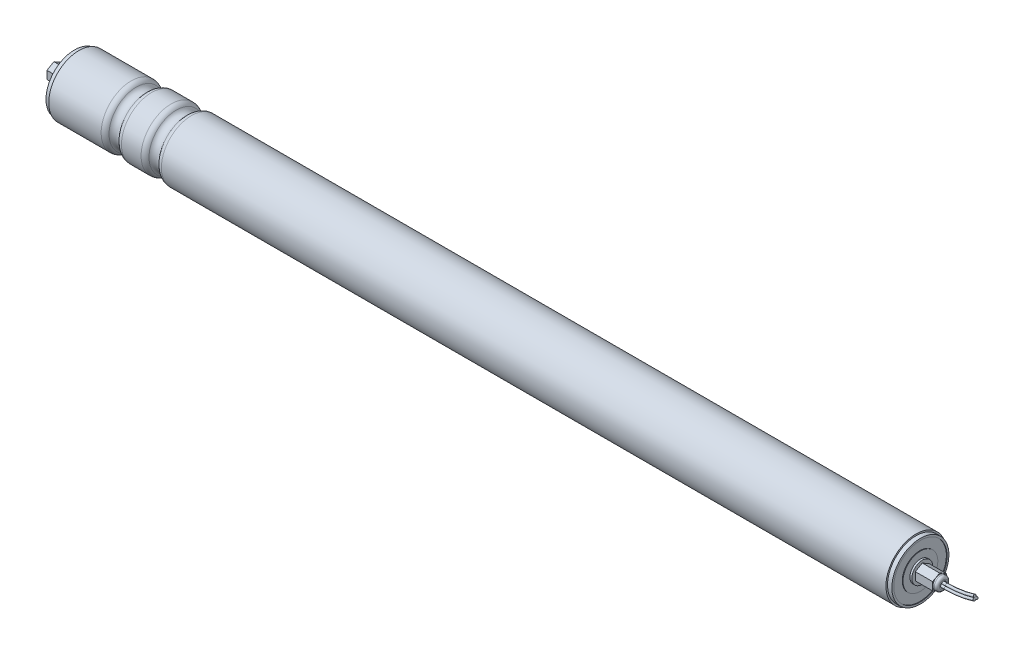
SolidWorks part; units mm, degrees
ref_plane "Front Plane" through (0, 0, 0) normal (0, 0, 1) x (1, 0, 0)
ref_plane "Top Plane" through (0, 0, 0) normal (0, 1, 0) x (1, 0, 0)
ref_plane "Right Plane" through (0, 0, 0) normal (1, 0, 0) x (0, 0, -1)
sketch "Sketch1" plane through (0, 0, 0) normal (0, 0, 1) x (1, 0, 0)
  line L0 (-340.407, 0) -> (340.407, 0) construction
  line L1 (-340.407, 0) -> (-355.393, 0) construction
  line L2 (340.407, 0) -> (357.425, 0) construction
  line L3 (-342.9, 0) -> (-340.407, 0) construction
  line L4 (340.407, 0) -> (342.9, 0) construction
  point P2 (-342.9, 0)
  point P6 (342.9, 0)
  point P7 (-335.407, 0)
  point P8 (335.407, 0)
  dimension "D1" = 17.018
  dimension "D2" = 14.986
  dimension "D3" = 5
  dimension "D4" = 5
  dimension "BF" = 685.8
  dimension "D5" = 670.814
sketch "Sketch2" plane through (0, 0, 0) normal (0, 0, 1) x (1, 0, 0)
  line L0 (-340.407, 0) -> (-340.407, 8.382)
  line L1 (-340.407, 8.382) -> (-338.883, 8.382)
  line L2 (-338.883, 8.382) -> (-338.883, 13.97)
  line L3 (-338.883, 13.97) -> (-338.375, 13.97)
  line L4 (-338.375, 13.97) -> (-338.375, 21.336)
  line L5 (-338.375, 21.336) -> (-338.883, 21.336)
  line L6 (-338.883, 21.336) -> (-338.883, 22.86)
  line L7 (-338.883, 22.86) -> (-335.407, 22.86)
  line L8 (-335.407, 22.86) -> (-335.407, 0)
  line L9 (-340.407, 0) -> (340.407, 0) construction
  line L10 (-335.407, 0) -> (-340.407, 0)
  line L11 (-340.407, 0) -> (-355.393, 0) construction
  line L12 (0, 0) -> (0, 29.0055) construction
  line L13 (335.407, 0) -> (340.407, 0)
  line L14 (335.407, 22.86) -> (335.407, 0)
  line L15 (338.883, 22.86) -> (335.407, 22.86)
  line L16 (338.883, 21.336) -> (338.883, 22.86)
  line L17 (338.375, 21.336) -> (338.883, 21.336)
  line L18 (338.375, 13.97) -> (338.375, 21.336)
  line L19 (338.883, 13.97) -> (338.375, 13.97)
  line L20 (338.883, 8.382) -> (338.883, 13.97)
  line L21 (340.407, 8.382) -> (338.883, 8.382)
  line L22 (340.407, 0) -> (340.407, 8.382)
  dimension "D1" = 16.764
  dimension "D2" = 27.94
  dimension "D3" = 45.72
  dimension "D4" = 0.508
  dimension "D5" = 1.524
  dimension "D6" = 1.524
revolve "Revolve1" add sketch "Sketch2" angle 360 mid plane about L11
sketch "Sketch3" plane through (-340.407, 0, 0) normal (-1, 0, 0) x (0, 0, 1)
  line L1 (0, 6.4158) -> (-5.5562, 3.2079)
  line L2 (-5.5562, 3.2079) -> (-5.5562, -3.2079)
  line L3 (-5.5562, -3.2079) -> (0, -6.4158)
  line L4 (0, -6.4158) -> (5.5562, -3.2079)
  line L5 (5.5562, -3.2079) -> (5.5562, 3.2079)
  line L6 (5.5562, 3.2079) -> (0, 6.4158)
  circle A0 centre (0, 0) radius 5.5563 construction
  dimension "D1" = 11.1125
extrude "Boss-Extrude1" add sketch "Sketch3" along normal up to vertex (14.986 mm away) up to point (-355.393, 0, 0)
sketch "Sketch4" plane through (340.407, 0, 0) normal (1, 0, 0) x (0, 0, -1)
  line L6 (5.5562, 3.2079) -> (0, 6.4158)
  line L7 (5.5562, -3.2079) -> (5.5562, 3.2079)
  line L8 (0, -6.4158) -> (5.5562, -3.2079)
  line L9 (-5.5562, -3.2079) -> (0, -6.4158)
  line L10 (-5.5562, 3.2079) -> (-5.5562, -3.2079)
  line L11 (0, 6.4158) -> (-5.5562, 3.2079)
  line L12 (5.5562, 3.2079) -> (0, 6.4158)
  line L13 (5.5562, -3.2079) -> (5.5562, 3.2079)
  line L14 (0, -6.4158) -> (5.5562, -3.2079)
  line L15 (-5.5562, -3.2079) -> (0, -6.4158)
  line L16 (-5.5562, 3.2079) -> (-5.5562, -3.2079)
  line L17 (0, 6.4158) -> (-5.5562, 3.2079)
  dimension "D1" = 0
extrude "Boss-Extrude2" add sketch "Sketch4" along normal up to vertex (17.018 mm away) up to point (357.425, 0, 0)
sketch "Sketch5" plane through (357.425, 0, 0) normal (1, 0, 0) x (0, 0, -1)
  circle A0 centre (0, 0) radius 5.334
  dimension "D1" = 10.668
extrude "Cut-Extrude1" cut sketch "Sketch5" against normal blind 3.175 flip side to cut
fillet "Fillet1" radius 2.032 1 edges at (357.425, 0, -5.334)
sketch "Sketch6" plane through (0, 0, 0) normal (1, 0, 0) x (0, 0, -1)
  circle A0 centre (0, 0) radius 24.13
  dimension "D1" = 48.26
extrude "Boss-Extrude3" add sketch "Sketch6" against normal up to surface and the other way up to surface up to face at (-335.407, 22.86, 0) other way up to face at (335.407, 22.86, 0)
sketch "Sketch7" plane through (0, 0, 0) normal (0, 0, 1) x (1, 0, 0)
  line L0 (-285.289, 19.558) -> (-285.289, 24.3205) construction
  line L1 (-293.4249, 24.13) -> (-277.1531, 24.13)
  line L2 (-285.289, 19.558) -> (-253.285, 19.558) construction
  line L3 (-253.285, 19.558) -> (-253.285, 26.4003) construction
  line L4 (-269.287, 19.558) -> (-269.287, 26.4003) construction
  line L5 (335.407, 24.13) -> (-335.407, 24.13) construction
  line L6 (-245.1491, 24.13) -> (-261.4209, 24.13)
  line L7 (-340.407, 8.382) -> (-340.407, -8.382) construction
  line L8 (-342.9, 0) -> (-355.393, 0) construction
  arc A0 (-293.4249, 24.13) -> (-289.357, 21.844) centre (-293.4249, 19.3675) cw
  arc A1 (-289.357, 21.844) -> (-281.221, 21.844) centre (-285.289, 24.3205) ccw
  arc A2 (-277.1531, 24.13) -> (-281.221, 21.844) centre (-277.1531, 19.3675) ccw
  arc A3 (-261.4209, 24.13) -> (-257.353, 21.844) centre (-261.4209, 19.3675) cw
  arc A4 (-249.217, 21.844) -> (-257.353, 21.844) centre (-253.285, 24.3205) cw
  arc A5 (-245.1491, 24.13) -> (-249.217, 21.844) centre (-245.1491, 19.3675) ccw
  point P9 (-285.289, 24.13)
  dimension "D1" = 4.7625
  dimension "D2" = 32.004
  dimension "D3" = 4.572
  dimension "D4" = 55.118
revolve "Cut-Revolve1" cut sketch "Sketch7" angle 360 mid plane about L8
sketch "Sketch8" plane through (357.425, 0, 0) normal (1, 0, 0) x (0, 0, -1)
  circle A0 centre (0, 0) radius 2.286
  dimension "D1" = 4.572
extrude "Cut-Extrude2" cut sketch "Sketch8" against normal blind 5.08
sketch "Sketch9" plane through (352.345, 0, 0) normal (1, 0, 0) x (0, 0, -1)
  line L0 (0, 1.143) -> (-0.9899, -0.5715) construction
  line L1 (-0.9899, -0.5715) -> (0.9899, -0.5715) construction
  line L2 (0.9899, -0.5715) -> (0, 1.143) construction
  line L3 (0, -0.5715) -> (0, 1.143) construction
  arc A0 (-0.2967, 0.1713) -> (0.2967, 0.1713) centre (0, 1.143) ccw construction
  arc A1 (-0.6932, 0.4002) -> (0, -0.8005) centre (-0.9899, -0.5715) ccw
  arc A2 (0, -0.8005) -> (0.6932, 0.4002) centre (0.9899, -0.5715) ccw
  circle A3 centre (0, 0) radius 2.159 construction
  arc A4 (0, -0.3425) -> (-0.2967, 0.1713) centre (-0.9899, -0.5715) ccw construction
  arc A5 (0.6932, 0.4002) -> (-0.6932, 0.4002) centre (0, 1.143) ccw
  arc A6 (0.2967, 0.1713) -> (0, -0.3425) centre (0.9899, -0.5715) ccw construction
  dimension "D1" = 4.318
  dimension "D2" = 2.032
sketch "Sketch10" plane through (0, 0, 0) normal (0, 0, 1) x (1, 0, 0)
  line L0 (352.345, 0) -> (359.965, 0)
  line L1 (352.345, -2.159) -> (352.345, 2.159) construction
  arc A0 (359.965, 0) -> (382.825, 3.5098) centre (359.965, 76.2) ccw
  dimension "D1" = 76.2
  dimension "D2" = 7.62
  dimension "D3" = 22.86
sweep "Sweep1" add profiles "Sketch9" path "Sketch10"
equation "\"D4@Sketch1\" = \"D3@Sketch1\""
equation "\"D5@Sketch1\" = \"BF@Sketch1\"-.590"
